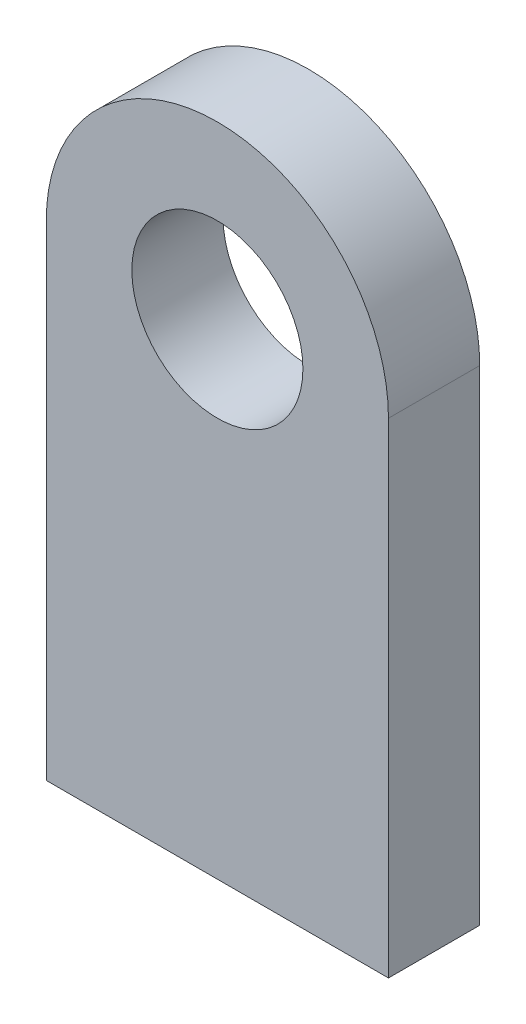
SolidWorks part; units mm, degrees
ref_plane "前视基准面" through (0, 0, 0) normal (0, 0, 1) x (1, 0, 0)
ref_plane "上视基准面" through (0, 0, 0) normal (0, 1, 0) x (1, 0, 0)
ref_plane "右视基准面" through (0, 0, 0) normal (1, 0, 0) x (0, 0, -1)
sketch "草图1" plane through (0, 0, 0) normal (0, 0, 1) x (1, 0, 0)
  line L0 (0, 0) -> (0, -28.1118) construction
  line L1 (30, 0) -> (30, -85)
  line L2 (-30, 0) -> (-30, -85)
  line L3 (30, -85) -> (-30, -85)
  arc A0 (30, 0) -> (-30, 0) centre (0, 0) ccw
  circle A2 centre (0, 0) radius 15
  point P3 (0, -14.0559)
  dimension "D1" = 30
  dimension "D2" = 30
  dimension "D3" = 85
extrude "凸台-拉伸1" add sketch "草图1" along normal blind 16
